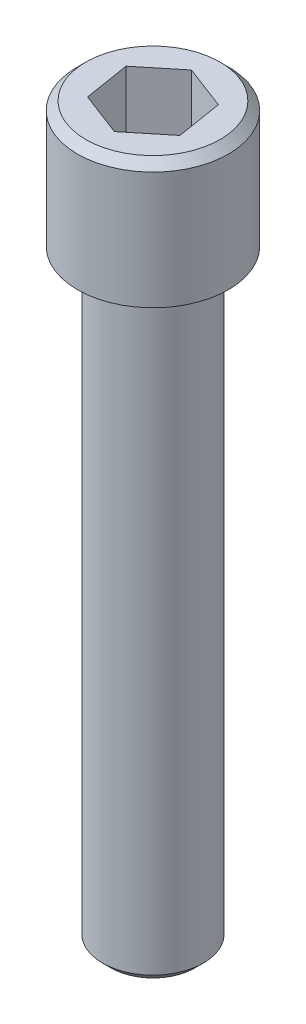
SolidWorks part; units mm, degrees
ref_plane "Přední rovina" through (0, 0, 0) normal (0, 0, 1) x (1, 0, 0)
ref_plane "Horní rovina" through (0, 0, 0) normal (0, 1, 0) x (1, 0, 0)
ref_plane "Pravá rovina" through (0, 0, 0) normal (1, 0, 0) x (0, 0, -1)
sketch "Skica1" plane through (0, 0, 0) normal (0, 1, 0) x (1, 0, 0)
  circle A0 centre (0, 0) radius 1.5
  dimension "D1" = 3
extrude "Přidat vysunutím1" add sketch "Skica1" along normal blind 18
sketch "Skica2" plane through (0, 18, 0) normal (0, 1, 0) x (1, 0, 0)
  circle A0 centre (0, 0) radius 2.25
  dimension "D1" = 4.5
extrude "Přidat vysunutím2" add sketch "Skica2" along normal blind 3.75
sketch "Skica3" plane through (0, 21.75, 0) normal (0, 1, 0) x (1, 0, 0)
  line L1 (-1.0744, -0.875) -> (0.2206, -1.368)
  line L2 (0.2206, -1.368) -> (1.295, -0.493)
  line L3 (1.295, -0.493) -> (1.0744, 0.875)
  line L4 (1.0744, 0.875) -> (-0.2206, 1.368)
  line L5 (-0.2206, 1.368) -> (-1.295, 0.493)
  line L6 (-1.295, 0.493) -> (-1.0744, -0.875)
  circle A0 centre (0, 0) radius 1.2 construction
  dimension "D1" = 2.4
extrude "Odebrat vysunutím1" cut sketch "Skica3" against normal blind 2.25
chamfer "Zkosení1" distance 0.25 angle 45 1 edges at (0, 21.75, 2.25)
chamfer "Zkosení2" distance 0.25 angle 45 1 edges at (0, 0, 1.5)
